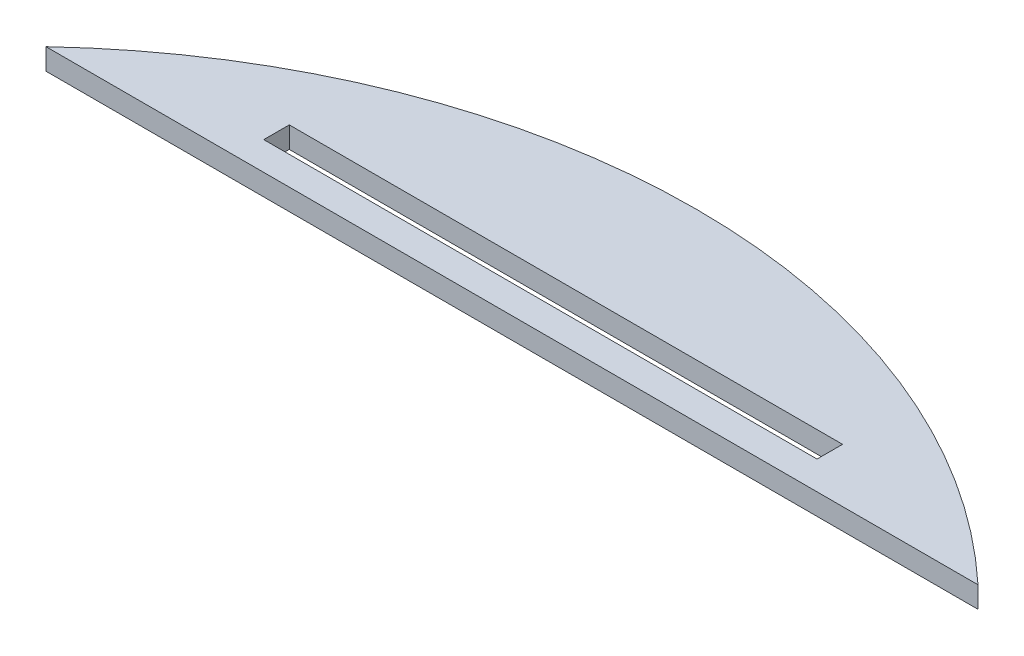
SolidWorks part; units mm, degrees
material "Balsa"
ref_plane "Front Plane" through (0, 0, 0) normal (0, 0, 1) x (1, 0, 0)
ref_plane "Top Plane" through (0, 0, 0) normal (0, 1, 0) x (1, 0, 0)
ref_plane "Right Plane" through (0, 0, 0) normal (1, 0, 0) x (0, 0, -1)
sketch "Sketch1" plane through (0, 0, 0) normal (0, 1, 0) x (1, 0, 0)
  circle A0 centre (0, 0) radius 48
  dimension "D1" = 96
extrude "Boss-Extrude1" add sketch "Sketch1" along normal blind 1.5
sketch "Sketch2" plane through (0, 1.5, 0) normal (0, 1, 0) x (1, 0, 0)
  line L0 (-32.8481, 35) -> (32.8481, 35)
  circle A0 centre (0, 0) radius 48 construction
  circle A2 centre (0, 0) radius 48
  arc A3 (-32.8481, 35) -> (32.8481, 35) centre (0, 0) ccw
  dimension "D2" = 13
  dimension "D1" = 0
extrude "Cut-Extrude1" cut sketch "Sketch2" against normal up to surface (1.5 mm away) up to face at (0, 0, 48)
sketch "Sketch3" plane through (0, 1.5, 0) normal (0, 1, 0) x (1, 0, 0)
  line L0 (32.8481, 35) -> (-32.8481, 35) construction
  line L1 (19.5, 38.8) -> (-19.5, 38.8)
  line L2 (19.5, 38.8) -> (19.5, 37)
  line L3 (19.5, 37) -> (-19.5, 37)
  line L4 (-19.5, 38.8) -> (-19.5, 37)
  point P6 (0, 35)
  point P7 (0, 38.8)
  dimension "D1" = 2
  dimension "D2" = 1.8
  dimension "D3" = 39
extrude "Cut-Extrude2" cut sketch "Sketch3" against normal up to surface (1.5 mm away) up to face at (0, 0, -41.5)
